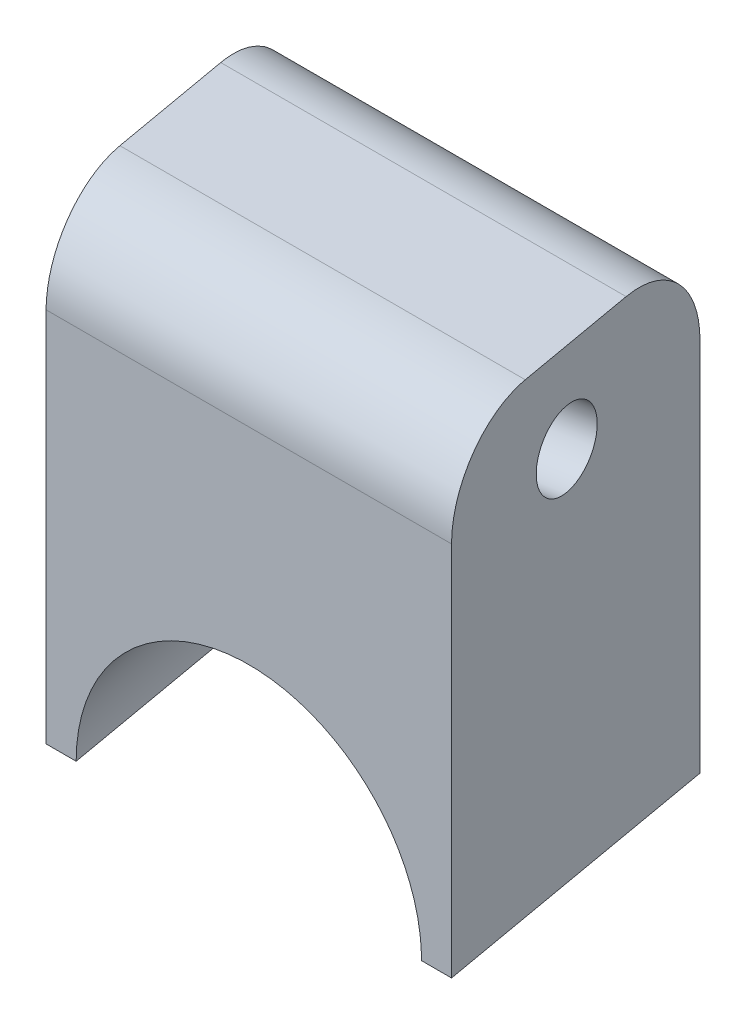
SolidWorks part; units mm, degrees
ref_plane "前视基准面" through (0, 0, 0) normal (0, 0, 1) x (1, 0, 0)
ref_plane "上视基准面" through (0, 0, 0) normal (0, 1, 0) x (1, 0, 0)
ref_plane "右视基准面" through (0, 0, 0) normal (1, 0, 0) x (0, 0, -1)
sketch "草图1" plane through (0, 0, 0) normal (0, 1, 0) x (1, 0, 0)
  line L1 (32.27, 35.1272) -> (54.915, 35.1272)
  line L5 (32.27, 35.1272) -> (35.2394, 18.287)
  line L6 (35.2394, 18.287) -> (57.8844, 18.287)
  line L7 (57.8844, 18.287) -> (54.915, 35.1272)
  line L8 (35.2394, 18.287) -> (35.9222, 14.4145)
  line L9 (35.9222, 14.4145) -> (57.8844, 18.287)
  dimension "D1" = 22.645
  dimension "D2" = 17.1
  dimension "D3" = 10
  dimension "D4" = 80
extrude "Boss-Extrude1" add sketch "草图1" along normal blind 26 contours L6 L7 L1 L5 | L8 L9 L6
sketch "Sketch1" plane through (-1.3818, 0, -7.8367) normal (0.1736, 0, 0.9848) x (0.9848, 0, -0.1736)
  line L0 (49.03, 0) -> (49.03, 13.8895) construction
  line L1 (37.8795, 0) -> (60.1805, 0) construction
  line L2 (39.53, 0) -> (58.53, 0)
  arc A0 (39.53, 0) -> (58.53, 0) centre (49.03, 0) cw
  dimension "D1" = 9.5
extrude "Cut-Extrude1" cut sketch "Sketch1" against normal blind 26
sketch "Sketch2" plane through (0, 26, 0) normal (0, 1, 0) x (1, 0, 0)
  line L0 (35.2394, 18.287) -> (35.9222, 14.4145)
  line L1 (35.9222, 14.4145) -> (57.8844, 18.287)
  line L2 (57.8844, 18.287) -> (35.2394, 18.287)
extrude "Cut-Extrude2" cut sketch "Sketch2" against normal blind 26
fillet "Fillet1" radius 5 2 edges at (46.5619, 26, -18.287) (43.5925, 26, -35.1272)
sketch "Sketch3" plane through (59.2662, 0, -10.4502) normal (0.9848, 0, -0.1736) x (-0.1736, 0, -0.9848)
  line L0 (13.0348, 26) -> (15.889, 26) construction
  line L1 (13.0348, 26) -> (19.9805, 26) construction
  line L2 (15.889, 26) -> (15.889, 20.2171) construction
  circle A0 centre (15.889, 21) radius 1
  dimension "D1" = 5
sketch "Sketch4" plane through (37.304, 0, -6.5777) normal (-0.9848, 0, 0.1736) x (0.1736, 0, 0.9848)
  line L0 (-16.967, 26) -> (-20.9247, 26) construction
  line L1 (-23.9128, 26) -> (-16.967, 26) construction
  line L2 (-20.9247, 26) -> (-20.9247, 18.2613) construction
  circle A0 centre (-20.9247, 21) radius 1
  dimension "D3" = 2
  dimension "D1" = 3.9577
  dimension "D2" = 5
hole_wizard "M5 Tapped Hole1" positions "3DSketch1" profile "Sketch5" tap size "M5" standard "GB"
sketch3d "3DSketch1"
  point P0 (33.6705, 21, -27.1845)
  point P3 (56.5071, 21, -26.0978)
sketch "Sketch5" plane through (33.6705, 21, -27.1845) normal (0, 1, 0) x (0.1736, 0, 0.9848)
  line L0 (0, 0) -> (0, 7.2618)
  line L1 (0, 7.2618) -> (2.1, 6)
  line L2 (2.1, 6) -> (2.1, 0)
  line L5 (2.1, 0) -> (0, 0)
  line L10 (0, 7.2618) -> (-2.1, 6) construction
  line L11 (0, -6.35) -> (0, 107.95) construction
  dimension "Tap Drill Dia." = 4.2
  dimension "Tap Drill Depth" = 6
  dimension "Drill Angle" = 118
cosmetic thread "Hole Thread1" parameters "D1"=6, "D2"=5
cosmetic thread "Hole Thread2" parameters "D1"=6, "D2"=5
